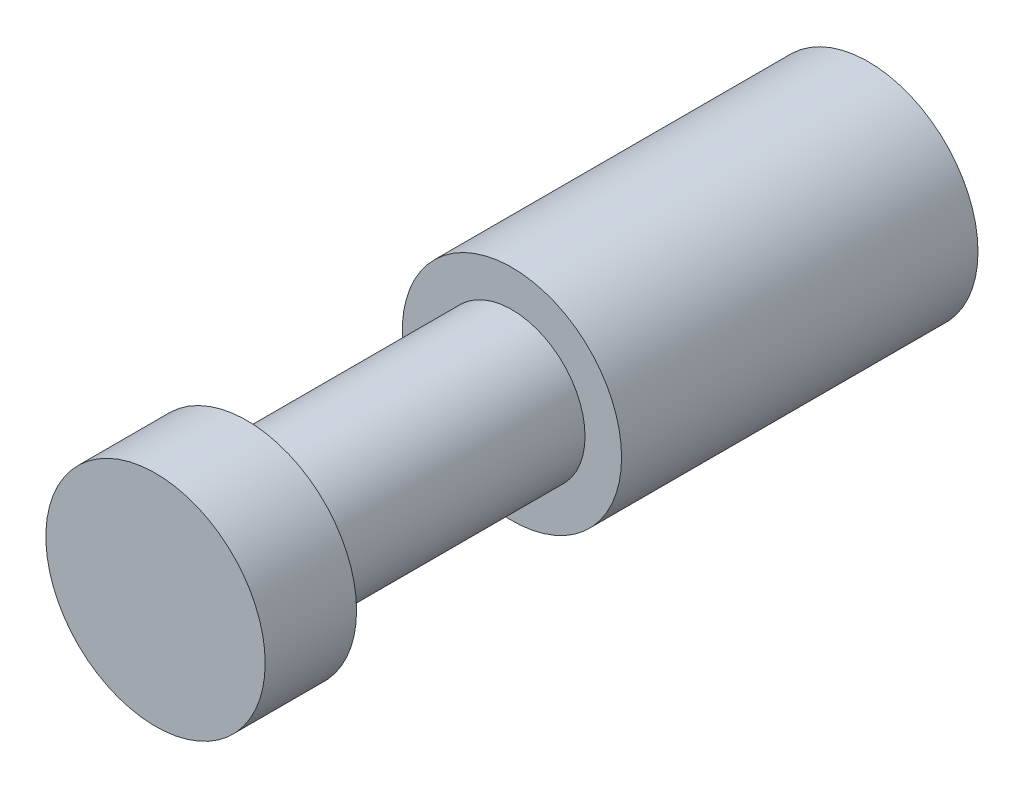
SolidWorks part; units mm, degrees
ref_plane "Front Plane" through (0, 0, 0) normal (0, 0, 1) x (1, 0, 0)
ref_plane "Top Plane" through (0, 0, 0) normal (0, 1, 0) x (1, 0, 0)
ref_plane "Right Plane" through (0, 0, 0) normal (1, 0, 0) x (0, 0, -1)
sketch "Sketch1" plane through (0, 0, 0) normal (0, 0, 1) x (1, 0, 0)
  circle A0 centre (0, 0) radius 4.4
  circle A1 centre (0, 0) radius 6
  dimension "D1" = 8.8
  dimension "D2" = 12
extrude "Boss-Extrude1" add sketch "Sketch1" along normal blind 12
sketch "Sketch2" plane through (0, 0, 12) normal (0, 0, 1) x (1, 0, 0)
  circle A0 centre (0, 0) radius 6
  circle A1 centre (0, 0) radius 6 construction
  dimension "D1" = 0
extrude "Boss-Extrude2" add sketch "Sketch2" along normal blind 2
sketch "Sketch3" plane through (0, 0, 14) normal (0, 0, 1) x (1, 0, 0)
  circle A0 centre (0, 0) radius 4
  dimension "D1" = 8
extrude "Boss-Extrude3" add sketch "Sketch3" along normal blind 20
sketch "Sketch4" plane through (0, 0, 34) normal (0, 0, 1) x (1, 0, 0)
  circle A0 centre (0, 0) radius 6
  dimension "D1" = 12
extrude "Boss-Extrude4" add sketch "Sketch4" along normal blind 5
sketch "Sketch5" plane through (0, 0, 14) normal (0, 0, 1) x (1, 0, 0)
  circle A0 centre (0, 0) radius 6
  circle A1 centre (0, 0) radius 6 construction
extrude "Boss-Extrude5" add sketch "Sketch5" along normal blind 5.5
